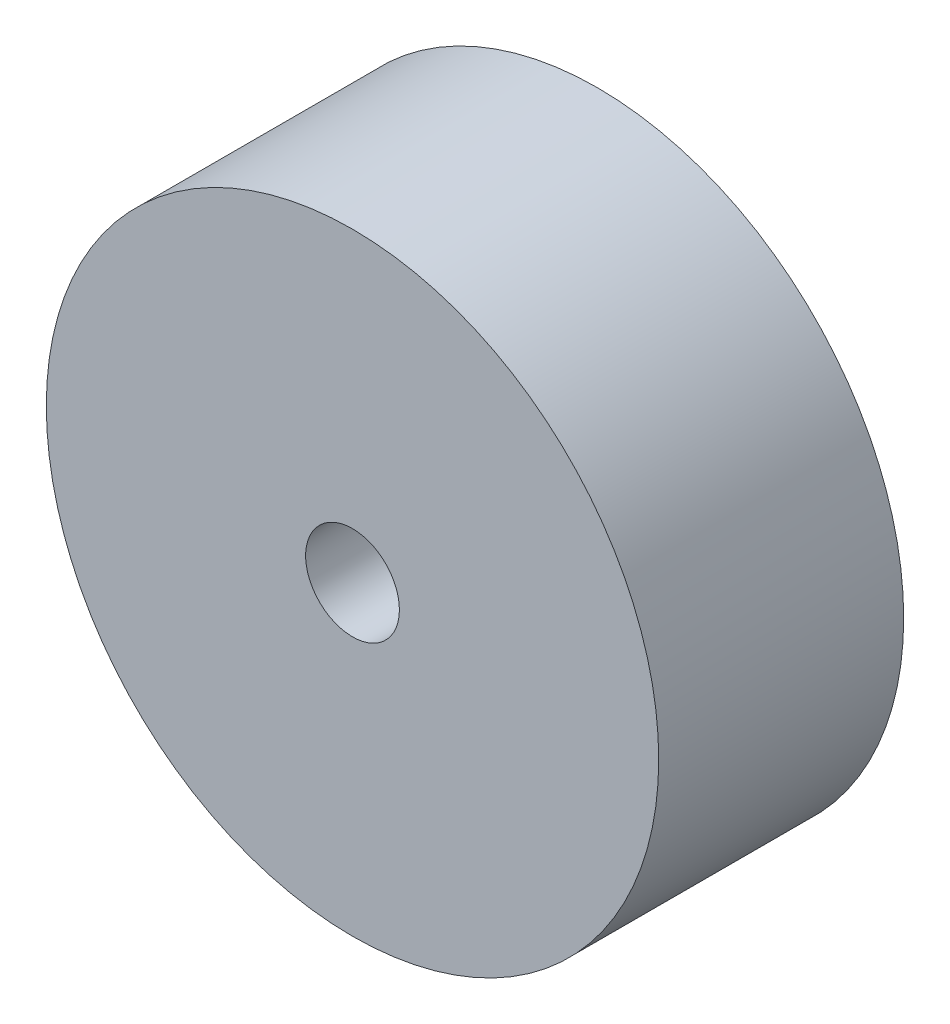
SolidWorks part; units mm, degrees
ref_plane "Front Plane" through (0, 0, 0) normal (0, 0, 1) x (1, 0, 0)
ref_plane "Top Plane" through (0, 0, 0) normal (0, 1, 0) x (1, 0, 0)
ref_plane "Right Plane" through (0, 0, 0) normal (1, 0, 0) x (0, 0, -1)
sketch "Sketch1" plane through (0, 0, 0) normal (0, 0, 1) x (1, 0, 0)
  circle A0 centre (-29.0823, -1.7038) radius 7.25
  dimension "D1" = 14.5
extrude "Boss-Extrude1" add sketch "Sketch1" along normal blind 5.8
sketch "Sketch2" plane through (0, 0, 0) normal (0, 0, -1) x (-1, 0, 0)
  circle A0 centre (29.0823, -1.7038) radius 6.325
  dimension "D1" = 12.65
extrude "Cut-Extrude1" cut sketch "Sketch2" against normal blind 1.5875
sketch "Sketch3" plane through (0, 0, 1.5875) normal (0, 0, -1) x (-1, 0, 0)
  circle A0 centre (29.0823, -1.7038) radius 1
  dimension "D1" = 2
extrude "Boss-Extrude2" add sketch "Sketch3" along normal blind 1.5875
sketch "Sketch4" plane through (0, 0, 0) normal (0, 0, -1) x (-1, 0, 0)
  circle A0 centre (29.0823, -1.7038) radius 3.15
  dimension "D1" = 6.3
extrude "Boss-Extrude3" add sketch "Sketch4" against normal blind 3
sketch "Sketch5" plane through (0, 0, 0) normal (0, 0, -1) x (-1, 0, 0)
  circle A0 centre (29.0823, -1.7038) radius 0.85
  dimension "D1" = 1.7
extrude "Cut-Extrude2" cut sketch "Sketch5" against normal through all
sketch "Sketch6" plane through (0, 0, 5.8) normal (0, 0, 1) x (1, 0, 0)
  circle A0 centre (-29.0823, -1.7038) radius 1.11
  dimension "D1" = 2.22
extrude "Cut-Extrude3" cut sketch "Sketch6" against normal blind 3
